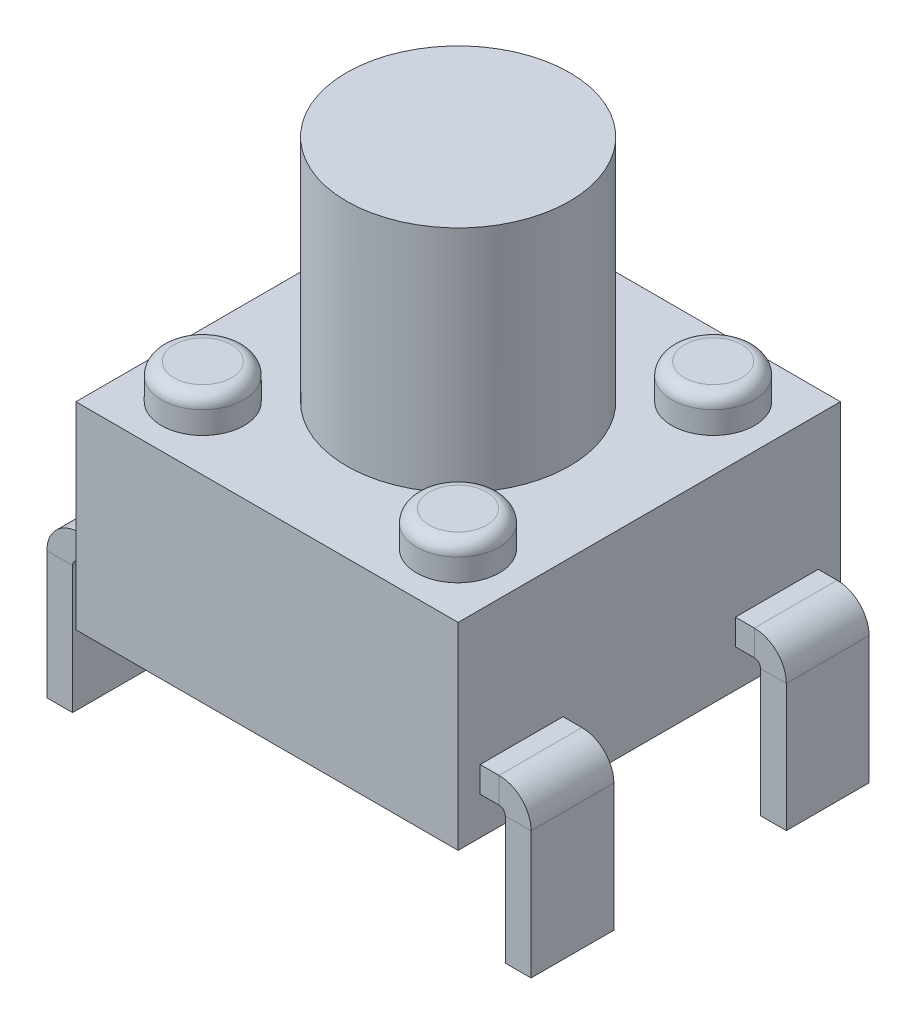
SolidWorks part; units mm, degrees
ref_plane "Спереди" through (0, 0, 0) normal (0, 0, 1) x (1, 0, 0)
ref_plane "Сверху" through (0, 0, 0) normal (0, 1, 0) x (1, 0, 0)
ref_plane "Справа" through (0, 0, 0) normal (1, 0, 0) x (0, 0, -1)
sketch "Эскиз1" plane through (0, 0, 0) normal (0, 1, 0) x (1, 0, 0)
  line L1 (-3, -3) -> (3, -3)
  line L2 (-3, -3) -> (-3, 3)
  line L3 (-3, 3) -> (3, 3)
  line L4 (3, -3) -> (3, 3)
  line L5 (-3, -3) -> (3, 3) construction
  line L6 (-3, 3) -> (3, -3) construction
  point P0 (0, 0)
  dimension "D1" = 6
  dimension "D2" = 6
extrude "Бобышка-Вытянуть1" add sketch "Эскиз1" along normal blind 3.1
sketch "Эскиз2" plane through (0, 3.1, 0) normal (0, 1, 0) x (1, 0, 0)
  circle A0 centre (0, 0) radius 1.75
  dimension "D1" = 3.5
extrude "Бобышка-Вытянуть2" add sketch "Эскиз2" along normal blind 3.6
sketch "Эскиз3" plane through (0, 3.1, 0) normal (0, 1, 0) x (1, 0, 0)
  line L0 (-3, -3) -> (-3, -2.004) construction
  line L1 (-3, 3) -> (-3, -3) construction
  line L2 (-3, -2.004) -> (-2.0043, -2.004) construction
  line L3 (-3, 3) -> (-2.0043, 3) construction
  line L4 (3, 3) -> (-3, 3) construction
  line L5 (-2.0043, 3) -> (-2.0043, 2.0023) construction
  line L6 (3, 3) -> (3, 2.0023) construction
  line L7 (3, -3) -> (3, 3) construction
  line L8 (3, 2.0023) -> (2.0013, 2.0023) construction
  line L9 (3, -3) -> (2.0013, -3) construction
  line L10 (-3, -3) -> (3, -3) construction
  line L11 (2.0013, -3) -> (2.0013, -2.004) construction
  line L12 (-2.0043, 2.6536) -> (-3, 2.6536) construction
  line L13 (-2.0043, 1.3511) -> (-3, 1.3511) construction
  line L14 (-2.0043, -1.354) -> (-3, -1.354) construction
  line L15 (-2.0043, -2.654) -> (-3, -2.654) construction
  line L16 (2.0013, -2.654) -> (3, -2.654) construction
  line L17 (2.0013, -1.354) -> (3, -1.354) construction
  line L18 (2.0013, 1.3523) -> (3, 1.3523) construction
  line L19 (2.0013, 2.6523) -> (3, 2.6523) construction
  circle A0 centre (-2.0043, -2.004) radius 0.65
  circle A1 centre (-2.0043, 2.0023) radius 0.6512
  circle A2 centre (2.0013, 2.0023) radius 0.65
  circle A3 centre (2.0013, -2.004) radius 0.65
  point P33 (-3, 2.6536)
  point P34 (-3, 1.3511)
  point P39 (-3, -1.354)
  point P40 (-3, -2.654)
  point P49 (3, -2.654)
  point P50 (3, -1.354)
  point P51 (3, 1.3523)
  point P52 (3, 2.6523)
sketch "Эскиз8" plane through (-3, 0, 0) normal (-1, 0, 0) x (0, 0, 1)
  line L0 (-2.6536, 3.1) -> (-2.6536, 1.0028) construction
  line L1 (-1.3511, 3.1) -> (-1.3511, 1.0028) construction
  line L2 (1.354, 3.1) -> (1.354, 1.0028) construction
  line L3 (2.654, 3.1) -> (2.654, 1.0028) construction
  line L4 (-2.6536, 1.0028) -> (-1.3511, 0.5996) construction
  line L5 (-1.3511, 1.0028) -> (-2.6536, 1.0028)
  line L6 (-1.3511, 1.0028) -> (-1.3511, 0.5996)
  line L7 (-1.3511, 0.5996) -> (-2.6536, 0.5996)
  line L8 (-2.6536, 1.0028) -> (-2.6536, 0.5996)
  line L9 (1.354, 1.0028) -> (2.654, 1.0028)
  line L10 (1.354, 1.0028) -> (1.354, 0.5996)
  line L11 (1.354, 0.5996) -> (2.654, 0.5996)
  line L12 (2.654, 1.0028) -> (2.654, 0.5996)
  point P7 (-2.6536, 1.0028)
  point P8 (-1.3511, 1.0028)
sketch "Эскиз11" plane through (0, 0, 0) normal (0, 0, 1) x (1, 0, 0)
  line L0 (-3, 0.8012) -> (-3.3, 0.8012)
  line L1 (-3, 1.0028) -> (-3, 0.5996) construction
  line L2 (-3.6, 0.5012) -> (-3.6, -1.4988)
  arc A0 (-3.3, 0.8012) -> (-3.6, 0.5012) centre (-3.3, 0.5012) ccw
  point P8 (-3, 0.8012)
  point P9 (-3.3, 0.8012)
  point P10 (-3.6, 0.5012)
  point P11 (-3.6, -1.4988)
  dimension "D1" = 0.3
ref_plane "Плоскость5" through (-3, 0.8012, 0) normal (-1, 0, 0) x (0, 0, 1)
sweep "По траектории11" add profiles "Эскиз8" path "Эскиз11"
extrude "Бобышка-Вытянуть5" add sketch "Эскиз3" along normal blind 0.55
fillet "Скругление1" radius 0.2 1 edges at (2.0013, 3.65, 2.654)
fillet "Скругление2" radius 0.2 1 edges at (-2.0043, 3.65, 2.654)
fillet "Скругление3" radius 0.2 1 edges at (2.0013, 3.65, -1.3523)
fillet "Скругление4" radius 0.2 1 edges at (-2.0043, 3.65, -1.3511)
sketch "Эскиз13" plane through (3, 0, 0) normal (1, 0, 0) x (0, 0, -1)
  line L0 (-2.654, 3.1) -> (-2.654, 0.9955) construction
  line L1 (-3, 3.1) -> (3, 3.1) construction
  line L2 (-1.3541, 3.1) -> (-1.3541, 0.9955) construction
  line L3 (1.3523, 3.1) -> (1.3523, 0.9955) construction
  line L4 (-2.654, 0.9955) -> (-1.3541, 0.9955)
  line L5 (-2.654, 0.9955) -> (-2.654, 0.5911)
  line L6 (-2.654, 0.5911) -> (-1.3541, 0.5911)
  line L7 (-1.3541, 0.9955) -> (-1.3541, 0.5911)
  line L8 (2.6523, 3.1) -> (2.6523, 0.9955) construction
  line L9 (-1.3541, 0.5911) -> (-2.654, 0.9955) construction
  line L10 (1.3523, 0.9955) -> (2.6523, 0.9955)
  line L11 (1.3523, 0.9955) -> (1.3523, 0.5911)
  line L12 (1.3523, 0.5911) -> (2.6523, 0.5911)
  line L13 (2.6523, 0.9955) -> (2.6523, 0.5911)
sketch "Эскиз14" plane through (0, 0, 0) normal (0, 0, 1) x (1, 0, 0)
  line L0 (3, 0.7933) -> (3.2968, 0.7933)
  line L1 (3, 0.9955) -> (3, 0.5911) construction
  line L2 (3.5968, 0.4933) -> (3.5968, -1.5075)
  arc A0 (3.2968, 0.7933) -> (3.5968, 0.4933) centre (3.2968, 0.4933) cw
  dimension "D1" = 0.3
ref_plane "Плоскость6" through (3, 0.7933, 0) normal (1, 0, 0) x (0, 0, -1)
sweep "По траектории12" add profiles "Эскиз13" path "Эскиз14"
